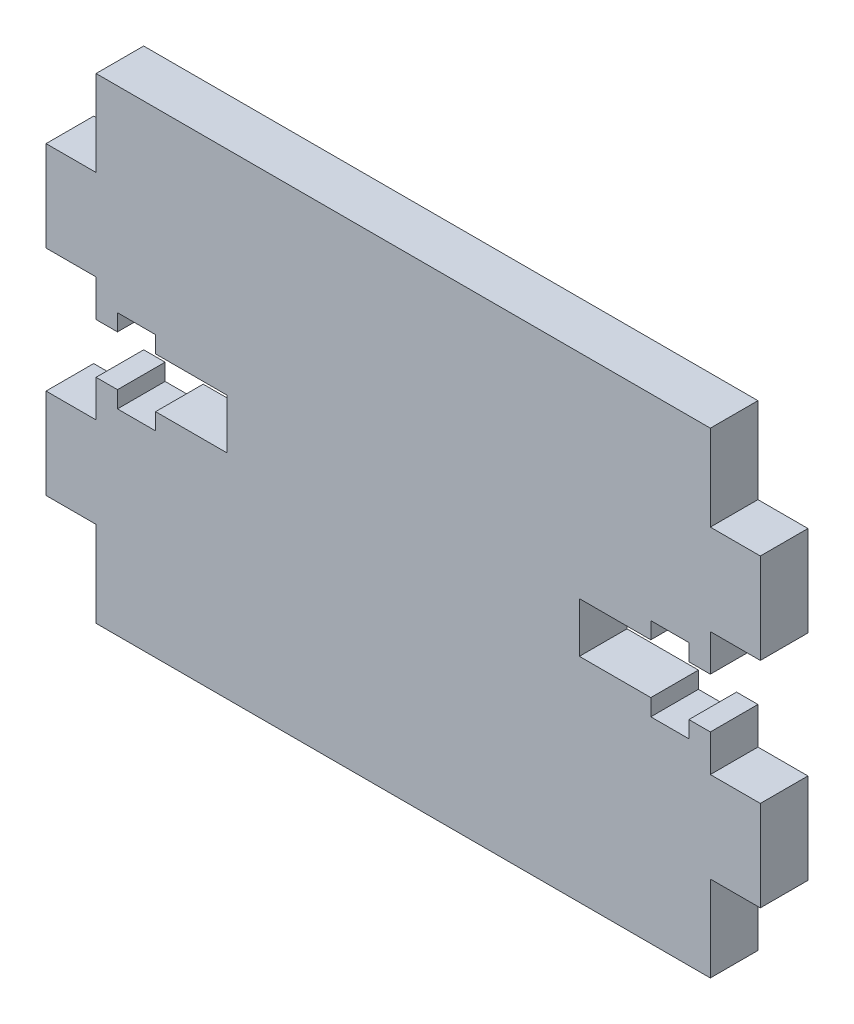
SolidWorks part; units mm, degrees
ref_plane "Plan de face" through (0, 0, 0) normal (0, 0, 1) x (1, 0, 0)
ref_plane "Plan de dessus" through (0, 0, 0) normal (0, 1, 0) x (1, 0, 0)
ref_plane "Plan de droite" through (0, 0, 0) normal (1, 0, 0) x (0, 0, -1)
sketch "Esquisse1" plane through (0, 0, 0) normal (0, 0, 1) x (1, 0, 0)
  line L1 (30, -20) -> (-30, -20)
  line L2 (30, -20) -> (30, 20)
  line L3 (30, 20) -> (-30, 20)
  line L4 (-30, -20) -> (-30, 20)
  line L5 (30, -20) -> (-30, 20) construction
  line L6 (30, 20) -> (-30, -20) construction
  point P0 (0, 0)
  dimension "D1" = 40
  dimension "D2" = 60
extrude "Boss.-Extru.1" add sketch "Esquisse1" along normal blind 4
sketch "Esquisse2" plane through (0, 0, 0) normal (0, 0, -1) x (-1, 0, 0)
  line L0 (0, 0) -> (0, -20) construction
  line L1 (-26, 13) -> (-30, 13) construction
  line L2 (-26, 13) -> (-26, 20) construction
  line L3 (-26, 20) -> (-30, 20) construction
  line L4 (-30, 13) -> (-30, 20) construction
  line L5 (-26, -13) -> (-30, -13) construction
  line L6 (-26, -13) -> (-26, -20) construction
  line L7 (-26, -20) -> (-30, -20) construction
  line L8 (-30, -13) -> (-30, -20) construction
  line L9 (30, -20) -> (-30, -20) construction
  line L10 (-30, -20) -> (-30, 20) construction
  line L11 (-26, 5) -> (-30, 5) construction
  line L12 (-26, 5) -> (-26, -5) construction
  line L13 (-26, -5) -> (-30, -5) construction
  line L14 (-30, 5) -> (-30, -5) construction
  line L15 (-26, 5) -> (-30, -5) construction
  line L16 (-26, -5) -> (-30, 5) construction
  line L17 (-28, 0) -> (0, 0) construction
  line L18 (-25.8, -12.8) -> (-30.2, -12.8)
  line L19 (-30.2, -12.8) -> (-30.2, -20.2)
  line L20 (-25.8, -20.2) -> (-30.2, -20.2)
  line L21 (-25.8, -12.8) -> (-25.8, -20.2)
  line L22 (-25.8, 12.8) -> (-30.2, 12.8)
  line L23 (-30.2, 12.8) -> (-30.2, 20.2)
  line L24 (-25.8, 20.2) -> (-30.2, 20.2)
  line L25 (-25.8, 12.8) -> (-25.8, 20.2)
  line L26 (-25.8, 5.2) -> (-30.2, 5.2)
  line L27 (-30.2, 5.2) -> (-30.2, -5.2)
  line L28 (-25.8, -5.2) -> (-30.2, -5.2)
  line L29 (-25.8, 5.2) -> (-25.8, -5.2)
  line L30 (26, -5) -> (30, 5) construction
  line L31 (26, 5) -> (30, -5) construction
  line L32 (30, 5) -> (30, -5) construction
  line L33 (26, -5) -> (30, -5) construction
  line L34 (26, 5) -> (26, -5) construction
  line L35 (26, 5) -> (30, 5) construction
  line L36 (30, -13) -> (30, -20) construction
  line L37 (26, -20) -> (30, -20) construction
  line L38 (26, -13) -> (26, -20) construction
  line L39 (26, -13) -> (30, -13) construction
  line L40 (30, 13) -> (30, 20) construction
  line L41 (26, 20) -> (30, 20) construction
  line L42 (26, 13) -> (26, 20) construction
  line L43 (26, 13) -> (30, 13) construction
  line L44 (25.8, 5.2) -> (25.8, -5.2)
  line L45 (25.8, -5.2) -> (30.2, -5.2)
  line L46 (30.2, 5.2) -> (30.2, -5.2)
  line L47 (25.8, 5.2) -> (30.2, 5.2)
  line L48 (25.8, 12.8) -> (25.8, 20.2)
  line L49 (25.8, 20.2) -> (30.2, 20.2)
  line L50 (30.2, 12.8) -> (30.2, 20.2)
  line L51 (25.8, 12.8) -> (30.2, 12.8)
  line L52 (25.8, -12.8) -> (25.8, -20.2)
  line L53 (25.8, -20.2) -> (30.2, -20.2)
  line L54 (30.2, -12.8) -> (30.2, -20.2)
  line L55 (25.8, -12.8) -> (30.2, -12.8)
  point P17 (-28, 0)
  point P24 (-28, 5)
  point P38 (28, 0)
  dimension "D1" = 10
  dimension "D2" = 0.2
extrude "Enlèv. mat.-Extru.1" cut sketch "Esquisse2" against normal through all
sketch "Esquisse3" plane through (0, 0, 0) normal (0, 0, -1) x (-1, 0, 0)
  line L0 (0, 20) -> (0, 0) construction
  line L1 (-25.8, 20) -> (25.8, 20) construction
  line L2 (0, 0) -> (-25.8, 0) construction
  line L3 (-25.8, -5.2) -> (-25.8, 5.2) construction
  line L4 (-25.8, -2.1) -> (-25.8, 2.1)
  line L5 (-25.8, 2.1) -> (-24, 2.1)
  line L6 (-24, 2.1) -> (-24, 3.5)
  line L7 (-24, 3.5) -> (-20.8, 3.5)
  line L8 (-20.8, 3.5) -> (-20.8, 2.1)
  line L9 (-20.8, 2.1) -> (-14.8, 2.1)
  line L10 (-14.8, 2.1) -> (-14.8, -2.1)
  line L11 (-20.8, -2.1) -> (-14.8, -2.1)
  line L12 (-20.8, -3.5) -> (-20.8, -2.1)
  line L13 (-24, -3.5) -> (-20.8, -3.5)
  line L14 (-24, -2.1) -> (-24, -3.5)
  line L15 (-25.8, -2.1) -> (-24, -2.1)
  line L16 (25.8, -2.1) -> (24, -2.1)
  line L17 (24, -2.1) -> (24, -3.5)
  line L18 (24, -3.5) -> (20.8, -3.5)
  line L19 (20.8, -3.5) -> (20.8, -2.1)
  line L20 (20.8, -2.1) -> (14.8, -2.1)
  line L21 (14.8, 2.1) -> (14.8, -2.1)
  line L22 (20.8, 2.1) -> (14.8, 2.1)
  line L23 (20.8, 3.5) -> (20.8, 2.1)
  line L24 (24, 3.5) -> (20.8, 3.5)
  line L25 (24, 2.1) -> (24, 3.5)
  line L26 (25.8, 2.1) -> (24, 2.1)
  line L27 (25.8, -2.1) -> (25.8, 2.1)
  point P16 (-14.8, 0)
  point P33 (14.8, 0)
  dimension "D1" = 4.2
  dimension "D2" = 7
  dimension "D3" = 3.2
  dimension "D4" = 5
  dimension "D5" = 11
extrude "Enlèv. mat.-Extru.2" cut sketch "Esquisse3" against normal through all
